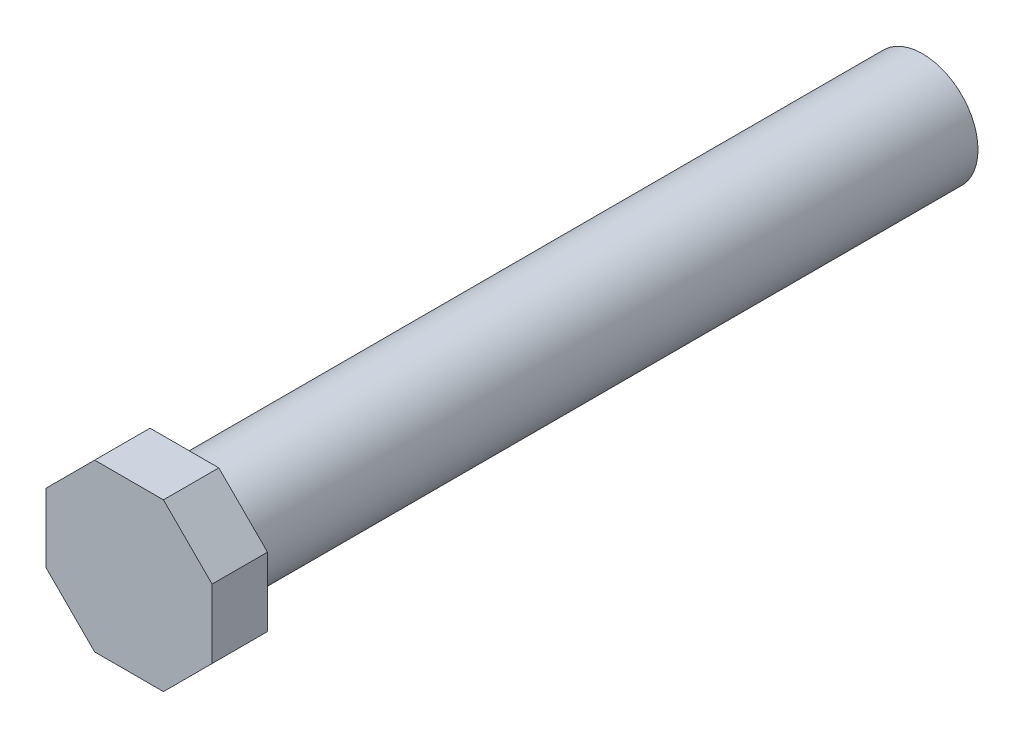
SolidWorks part; units mm, degrees
ref_plane "Front Plane" through (0, 0, 0) normal (0, 0, 1) x (1, 0, 0)
ref_plane "Top Plane" through (0, 0, 0) normal (0, 1, 0) x (1, 0, 0)
ref_plane "Right Plane" through (0, 0, 0) normal (1, 0, 0) x (0, 0, -1)
sketch "Sketch1" plane through (0, 0, 0) normal (0, 0, 1) x (1, 0, 0)
  circle A0 centre (0, 0) radius 3
  dimension "D1" = 6
extrude "Boss-Extrude1" add sketch "Sketch1" along normal blind 40
cosmetic thread "Cosmetic Thread1" parameters "D1"=30, "D2"=4.891
sketch "Sketch2" plane through (0, 0, 40) normal (0, 0, 1) x (1, 0, 0)
  line L0 (-1.864, -4.5) -> (1.864, -4.5)
  line L1 (4.5, -1.864) -> (4.5, 1.864)
  line L2 (4.5, 1.864) -> (1.864, 4.5)
  line L3 (1.864, 4.5) -> (-1.864, 4.5)
  line L4 (-1.864, 4.5) -> (-4.5, 1.864)
  line L5 (-4.5, 1.864) -> (-4.5, -1.864)
  line L6 (-4.5, -1.864) -> (-1.864, -4.5)
  line L7 (1.864, -4.5) -> (4.5, -1.864)
  circle A0 centre (0, 0) radius 4.5 construction
  dimension "D1" = 9
extrude "Boss-Extrude2" add sketch "Sketch2" along normal blind 3
equation "\"shaft inner diameter\"= 15mm "
equation "\"shaft outer diameter\"= 20mm "
equation "\"column angle\" = 45deg "
equation "\"keyway_height\" = 1.39mm "
equation "\"keyway_width\" = 2.78mm "
equation "\"keyway_length\" = 30mm "
equation "\"steering column length\" = 555mm "
equation "\"steering wheel bolt width\" = 6mm "
equation "\"steering wheel bolt length\" = 40mm "
equation "\"bushing length\" = 40mm "
equation "\"bushing thickness\" = 3mm "
equation "\"u_joint clearance\" = 30mm "
equation "\"u_joint thickness\" = 7.5mm "
equation "\"horizontal shaft length\" = 90mm "
equation "\"short_bearing_outer_width\" = 10mm "
equation "\"column bushing diameter\" = \"primary shaft small diameter\" + 4 "
equation "\"column bushing distance\" = \"steering column length\"/4 "
equation "\"pinion width\" = 26.5mm "
equation "\"number of teeth\" = 18mm "
equation "\"D1@Sketch1\"=\"steering wheel bolt width\""
equation "\"D1@Boss-Extrude1\"=\"steering wheel bolt length\""
equation "\"D1@Sketch2\"=\"steering wheel bolt width\"*1.5"
equation "\"wheel base\" = 1561mm "
equation "\"track\" = 1354mm "
equation "\"turning radius\" = 2000mm "
equation "\"turn to lock\" = 0.75mm "
equation "\"steering arm length\" = 100mm "
equation "\"primary shaft small diameter\" = 16mm "
equation "\"primary shaft large diameter\" = 24mm "
equation "\"secondary shaft small diameter\" = 16mm "
equation "\"secondary shaft large diameter\" = 25mm "
equation "\"pin hole diameter\" = 10mm "
equation "\"rack hole to hole\" = 500mm "
equation "\"rack length\" = \"rack hole to hole\" + \"pin hole diameter\"*2 "
equation "\"max turning angle\" = atn(\"wheel base\" / (\"turning radius\" - 0.5 * \"track\")) "
equation "\"max travel\" = 2 * \"steering arm length\" * sin(0.5 * \"max turning angle\") "
equation "\"pitch diameter\" = \"max travel\"/(pi * \"turn to lock\") "
equation "\"pressure angle\" = 20deg "
equation "\"module\" = \"pitch diameter\" / \"number of teeth\" "
equation "\"tie rod length\" = 305mm "
equation "\"tie rod inner diameter\" = 6.6mm "
equation "\"tie rod outer diameter\" = 8.1mm "
